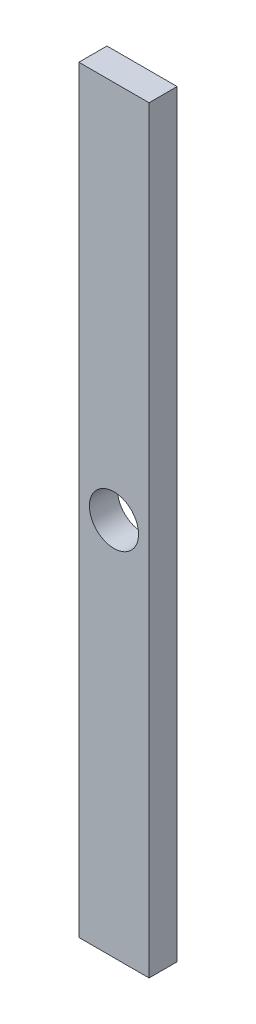
SolidWorks part; units mm, degrees
ref_plane "Front Plane" through (0, 0, 0) normal (0, 0, 1) x (1, 0, 0)
ref_plane "Top Plane" through (0, 0, 0) normal (0, 1, 0) x (1, 0, 0)
ref_plane "Right Plane" through (0, 0, 0) normal (1, 0, 0) x (0, 0, -1)
sketch "Sketch2" plane through (0, 0, 0) normal (0, 0, 1) x (1, 0, 0)
  line L1 (-2.5, 27) -> (2.5, 27)
  line L2 (-2.5, 27) -> (-2.5, -27)
  line L3 (-2.5, -27) -> (2.5, -27)
  line L4 (2.5, 27) -> (2.5, -27)
  line L5 (-2.5, 27) -> (2.5, -27) construction
  line L6 (-2.5, -27) -> (2.5, 27) construction
  point P0 (0, 0)
extrude "Boss-Extrude1" add sketch "Sketch2" along normal blind 2
sketch "Sketch3" plane through (0, 0, 2) normal (0, 0, 1) x (1, 0, 0)
  circle A0 centre (0, 0) radius 1.75
extrude "Cut-Extrude1" cut sketch "Sketch3" against normal blind 10 contours A0
